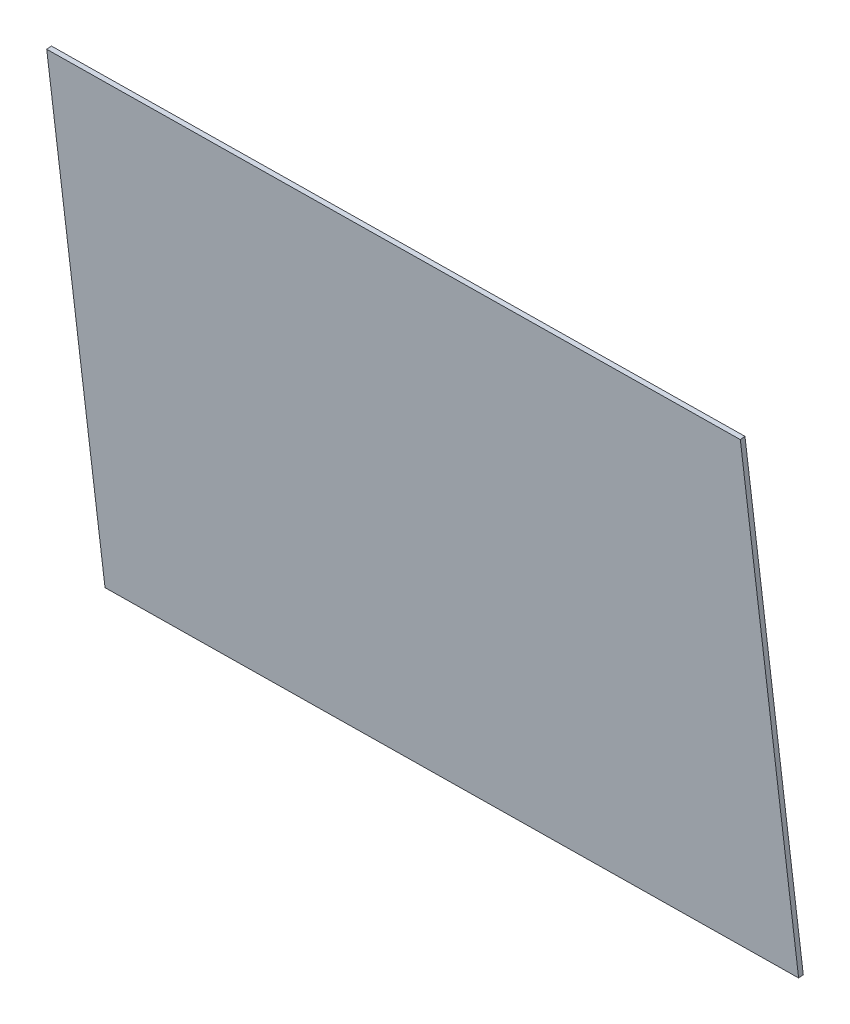
SolidWorks part; units mm, degrees
ref_plane "Front Plane" through (0, 0, 0) normal (0, 0, 1) x (1, 0, 0)
ref_plane "Top Plane" through (0, 0, 0) normal (0, 1, 0) x (1, 0, 0)
ref_plane "Right Plane" through (0, 0, 0) normal (1, 0, 0) x (0, 0, -1)
sketch "Sketch1" plane through (0, 20.8955, -198.807) normal (0, -0.1045, 0.9945) x (1, 0, 0)
  line L1 (129.9056, -701.7963) -> (426.8758, -697.5866)
  line L2 (129.9056, -701.7963) -> (132.8821, -911.7752)
  line L3 (132.8821, -911.7752) -> (429.8523, -907.5655)
  line L4 (426.8758, -697.5866) -> (429.8523, -907.5655)
  line L5 (129.9056, -701.7963) -> (429.8523, -907.5655) construction
  line L6 (132.8821, -911.7752) -> (426.8758, -697.5866) construction
  point P4 (279.8789, -804.6809)
  point P7 (0, 0)
  point P8 (0, 0)
  point P9 (124.3881, -751.6281)
  point P10 (-155.7135, -873.5101)
  point P11 (0, 0)
  point P13 (0, 0)
  point P15 (0, 0)
extrude "Boss-Extrude1" add sketch "Sketch1" along normal blind 2
